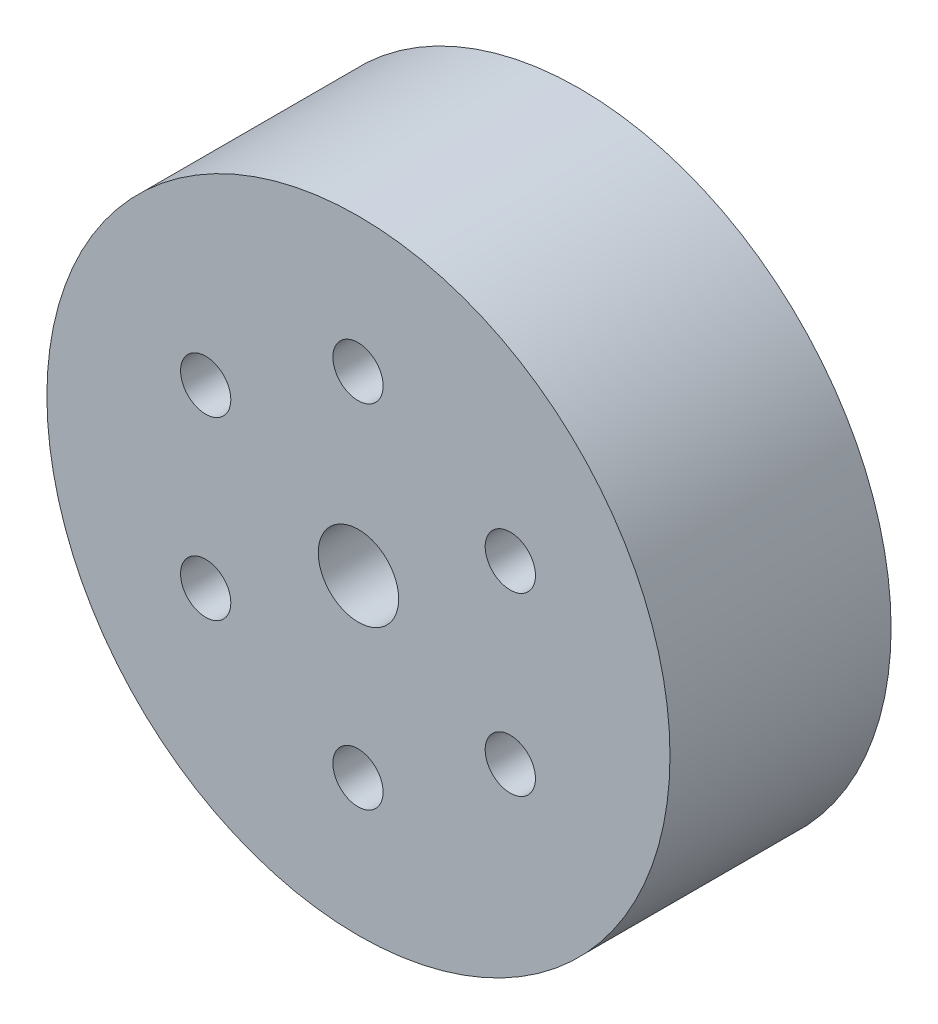
SolidWorks part; units mm, degrees
material "1023 Carbon Steel Sheet (SS)"
ref_plane "Front Plane" through (0, 0, 0) normal (0, 0, 1) x (1, 0, 0)
ref_plane "Top Plane" through (0, 0, 0) normal (0, 1, 0) x (1, 0, 0)
ref_plane "Right Plane" through (0, 0, 0) normal (1, 0, 0) x (0, 0, -1)
sketch "Sketch1" plane through (0, 0, 0) normal (0, 0, 1) x (1, 0, 0)
  circle A0 centre (0, 0) radius 15.5
  dimension "D1" = 31
extrude "Boss-Extrude1" add sketch "Sketch1" along normal blind 11
sketch "Sketch2" plane through (0, 0, 11) normal (0, 0, 1) x (1, 0, 0)
  circle A0 centre (0, 0) radius 2
  circle A1 centre (7.5553, 4.4136) radius 1.25
  circle A2 centre (7.5551, -4.3364) radius 1.25
  circle A3 centre (-0.0228, -8.7112) radius 1.25
  circle A4 centre (-7.6004, -4.336) radius 1.25
  circle A5 centre (-7.6001, 4.414) radius 1.25
  circle A6 centre (-0.0223, 8.7888) radius 1.25
  point P5 (-0.0225, 8.7888)
  point P18 (-0.0225, 0.0388)
  dimension "D1" = 4
  dimension "D2" = 2.5
  dimension "D4" = 17.5
  dimension "D5" = 8.75
  dimension "D3" = 6
extrude "Cut-Extrude1" cut sketch "Sketch2" against normal blind 11
